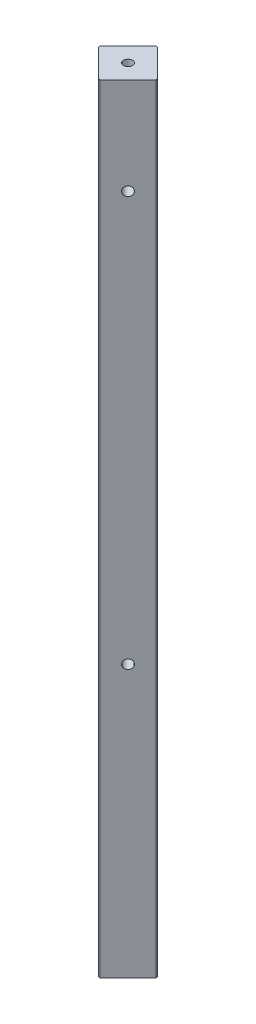
SolidWorks part; units mm, degrees
material "Alliage 1060"
ref_plane "Plan de face" through (0, 0, 0) normal (0, 0, 1) x (1, 0, 0)
ref_plane "Plan de dessus" through (0, 0, 0) normal (0, 1, 0) x (1, 0, 0)
ref_plane "Plan de droite" through (0, 0, 0) normal (1, 0, 0) x (0, 0, -1)
sketch "Esquisse1" plane through (0, 0, 0) normal (0, 1, 0) x (1, 0, 0)
  line L0 (0, -10.6066) -> (0, 10.6066) construction
  line L1 (0.3536, 10.253) -> (10.253, 0.3536)
  line L2 (-0.3536, 10.253) -> (-10.253, 0.3536)
  line L3 (-10.253, -0.3536) -> (-0.3536, -10.253)
  line L4 (10.253, -0.3536) -> (0.3536, -10.253)
  arc A0 (10.253, 0.3536) -> (10.253, -0.3536) centre (9.8995, 0) cw
  arc A1 (0.3536, 10.253) -> (-0.3536, 10.253) centre (0, 9.8995) ccw
  arc A2 (-10.253, 0.3536) -> (-10.253, -0.3536) centre (-9.8995, 0) ccw
  arc A3 (-0.3536, -10.253) -> (0.3536, -10.253) centre (0, -9.8995) ccw
  dimension "D1" = 0.5
  dimension "D2" = 15
  dimension "D3" = 15
extrude "Extrusion1" add sketch "Esquisse1" along normal up to surface (282 mm away)
hole_wizard "Trou taraudé M4x0.72" positions "Esquisse9" profile "Esquisse8" tap size "M4x0.7" standard "Ansi Métrique"
sketch "Esquisse9" plane through (0, 0, 0) normal (0, -1, 0) x (1, 0, 0)
  point P0 (0, 0)
sketch "Esquisse8" plane through (0, 0, 0) normal (1, 0, 0) x (0, 0, -1)
  line L0 (0, 0) -> (0, 18.0914)
  line L1 (0, 18.0914) -> (1.65, 17.1)
  line L2 (1.65, 17.1) -> (1.65, 0)
  line L5 (1.65, 0) -> (0, 0)
  line L10 (0, 18.0914) -> (-1.65, 17.1) construction
  line L11 (0, -6.35) -> (0, 107.95) construction
  dimension "Diamètre du trou pour taraudage" = 3.3
  dimension "Profondeur du trou pour taraudage" = 17.1
  dimension "Angle de pointe" = 118
cosmetic thread "Filetage de perçage2" parameters "D1"=12.8134, "D2"=4
hole_wizard "Trou taraudé M4x0.73" positions "Esquisse11" profile "Esquisse10" tap size "M4x0.7" standard "Ansi Métrique"
sketch "Esquisse11" plane through (0, 282, 0) normal (0, 1, 0) x (-1, 0, 0)
  point P0 (0, 0)
sketch "Esquisse10" plane through (0, 282, 0) normal (1, 0, 0) x (0, 0, 1)
  line L0 (0, 0) -> (0, 10.0914)
  line L1 (0, 10.0914) -> (1.65, 9.1)
  line L2 (1.65, 9.1) -> (1.65, 0)
  line L5 (1.65, 0) -> (0, 0)
  line L10 (0, 10.0914) -> (-1.65, 9.1) construction
  line L11 (0, -6.35) -> (0, 107.95) construction
  dimension "Diamètre du trou pour taraudage" = 3.3
  dimension "Profondeur du trou pour taraudage" = 9.1
  dimension "Angle de pointe" = 118
cosmetic thread "Filetage de perçage3" parameters "D1"=7, "D2"=4
hole_wizard "Trou taraudé M4x0.74" positions "Esquisse13" profile "Esquisse14" tap size "M4x0.7" standard "Ansi Métrique" end condition through all
sketch "Esquisse13" plane through (-5.3033, 0, 5.3033) normal (-0.7071, 0, 0.7071) x (0.7071, 0, 0.7071)
  circle A1 centre (0, 32) radius 2.1 construction
  circle A2 centre (0, 91) radius 2.1 construction
  point P0 (0, 91)
  point P1 (0, 32)
sketch "Esquisse14" plane through (-5.3033, 91, 5.3033) normal (0, 1, 0) x (0.7071, 0, 0.7071)
  line L0 (0, 0) -> (0, 22.2071)
  line L1 (0, 22.2071) -> (1.65, 22.2071)
  line L2 (1.65, 22.2071) -> (1.65, 0)
  line L5 (1.65, 0) -> (0, 0)
  line L11 (0, -6.35) -> (0, 107.95) construction
  dimension "Diamètre du trou pour taraudage jusqu'au prochain" = 3.3
  dimension "Profondeur du trou pour taraudage jusqu'au prochain" = 22.2071
cosmetic thread "Filetage de perçage4" parameters "D2"=4
cosmetic thread "Filetage de perçage5" parameters "D2"=4
hole_wizard "Trou taraudé M4x0.75" positions "Esquisse16" profile "Esquisse15" tap size "M4x0.7" standard "Ansi Métrique" end condition through all
sketch "Esquisse16" plane through (-5.3033, 0, -5.3033) normal (-0.7071, 0, -0.7071) x (-0.7071, 0, 0.7071)
  circle A0 centre (0, 247) radius 2 construction
  circle A1 centre (0, 98.5) radius 2 construction
  point P0 (0, 98.5)
  point P1 (0, 247)
sketch "Esquisse15" plane through (-5.3033, 98.5, -5.3033) normal (0, 1, 0) x (-0.7071, 0, 0.7071)
  line L0 (0, 0) -> (0, 22.2071)
  line L1 (0, 22.2071) -> (1.65, 22.2071)
  line L2 (1.65, 22.2071) -> (1.65, 0)
  line L5 (1.65, 0) -> (0, 0)
  line L11 (0, -6.35) -> (0, 107.95) construction
  dimension "Diamètre du trou pour taraudage jusqu'au prochain" = 3.3
  dimension "Profondeur du trou pour taraudage jusqu'au prochain" = 22.2071
cosmetic thread "Filetage de perçage6" parameters "D2"=4
cosmetic thread "Filetage de perçage7" parameters "D2"=4
hole_wizard "Trou taraudé M4x0.76" positions "Esquisse18" profile "Esquisse17" tap size "M4x0.7" standard "Ansi Métrique" end condition through all
sketch "Esquisse18" plane through (5.3033, 0, -5.3033) normal (0.7071, 0, -0.7071) x (-0.7071, 0, -0.7071)
  circle A0 centre (0, 252.6) radius 2 construction
  circle A1 centre (0, 268.6) radius 2 construction
  point P0 (0, 268.6)
  point P1 (0, 252.6)
sketch "Esquisse17" plane through (5.3033, 268.6, -5.3033) normal (0, 1, 0) x (-0.7071, 0, -0.7071)
  line L0 (0, 0) -> (0, 22.2071)
  line L1 (0, 22.2071) -> (1.65, 22.2071)
  line L2 (1.65, 22.2071) -> (1.65, 0)
  line L5 (1.65, 0) -> (0, 0)
  line L11 (0, -6.35) -> (0, 107.95) construction
  dimension "Diamètre du trou pour taraudage jusqu'au prochain" = 3.3
  dimension "Profondeur du trou pour taraudage jusqu'au prochain" = 22.2071
cosmetic thread "Filetage de perçage8" parameters "D2"=4
cosmetic thread "Filetage de perçage9" parameters "D2"=4
